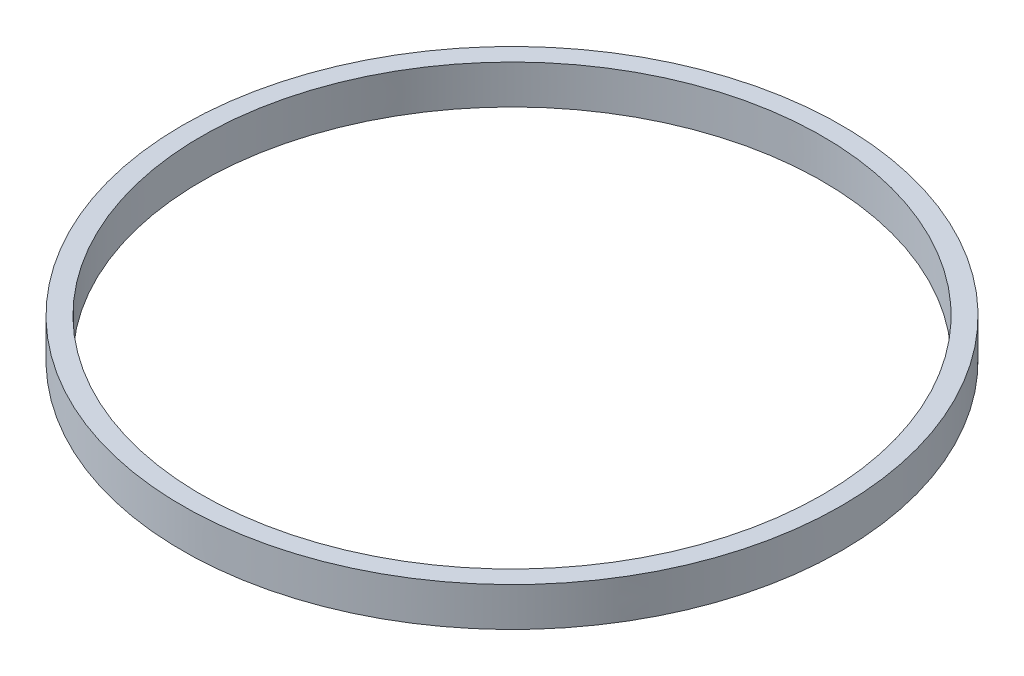
SolidWorks part; units mm, degrees
material "EPİKLORHİDRİN"
ref_plane "Ön Düzlem" through (0, 0, 0) normal (0, 0, 1) x (1, 0, 0)
ref_plane "Üst Düzlem" through (0, 0, 0) normal (0, 1, 0) x (1, 0, 0)
ref_plane "Sağ Düzlem" through (0, 0, 0) normal (1, 0, 0) x (0, 0, -1)
sketch "Çizim1" plane through (0, 0, 0) normal (0, 0, 1) x (1, 0, 0)
  line L0 (0, 0) -> (-0.0001, 2.0361) construction
  line L1 (17.2372, 0.0009) -> (17.237, 2.037)
  line L2 (17.237, 2.037) -> (16.2409, 2.0369)
  line L3 (16.2409, 2.0369) -> (16.2411, 0.0008)
  line L4 (16.2411, 0.0008) -> (17.2372, 0.0009)
revolve "Döndür1" add sketch "Çizim1" angle 360 about L0
